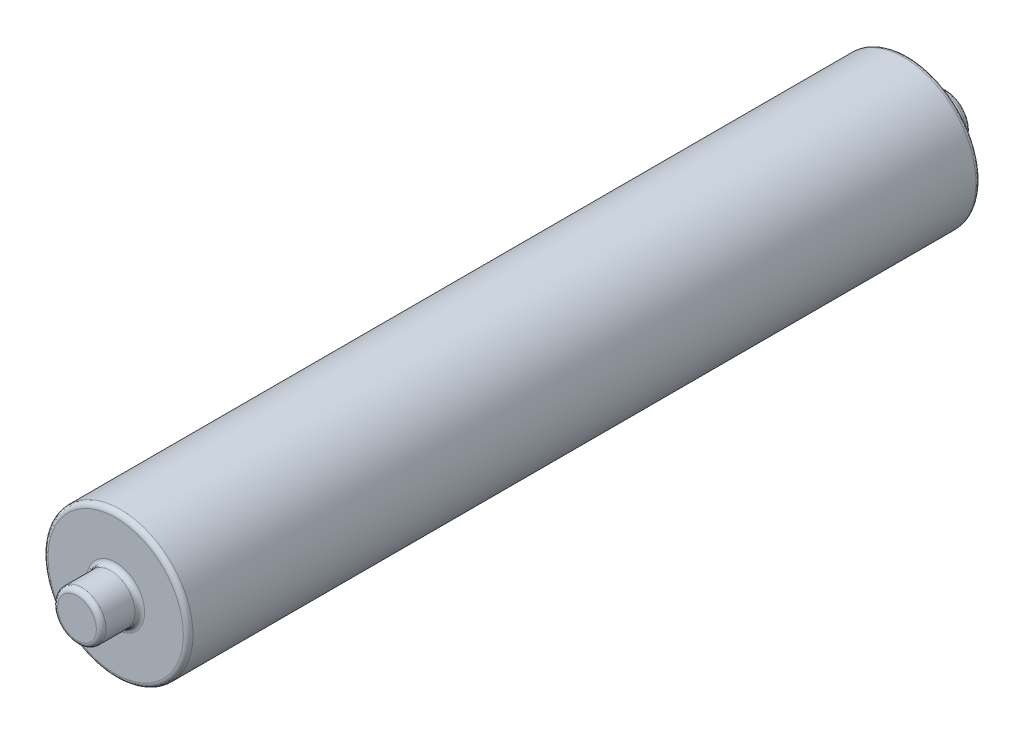
SolidWorks part; units mm, degrees
ref_plane "Alzado" through (0, 0, 0) normal (0, 0, 1) x (1, 0, 0)
ref_plane "Planta" through (0, 0, 0) normal (0, 1, 0) x (1, 0, 0)
ref_plane "Vista lateral" through (0, 0, 0) normal (1, 0, 0) x (0, 0, -1)
sketch "Croquis1" plane through (0, 0, 0) normal (0, 0, 1) x (1, 0, 0)
  circle A0 centre (0, 0) radius 3.75
  dimension "D1" = 7.5
extrude "Saliente-Extruir1" add sketch "Croquis1" along normal blind 41
sketch "Croquis2" plane through (0, 0, 0) normal (0, 0, -1) x (-1, 0, 0)
  circle A0 centre (0, 0) radius 1.25
  dimension "D1" = 2.5
extrude "Saliente-Extruir2" add sketch "Croquis2" along normal blind 2
sketch "Croquis3" plane through (0, 0, -2) normal (0, 0, -1) x (-1, 0, 0)
  circle A0 centre (0, 0) radius 1.25
extrude "Saliente-Extruir3" add sketch "Croquis3" along normal blind 0.0001 and the other way blind 45
fillet "Redondeo9" radius 0.25 6 edges at (-1.25, 0, 43) (-1.25, 0, -2.0001) (3.75, 0, 0) (3.75, 0, 41) (1.25, 0, 0) (1.25, 0, 41)
